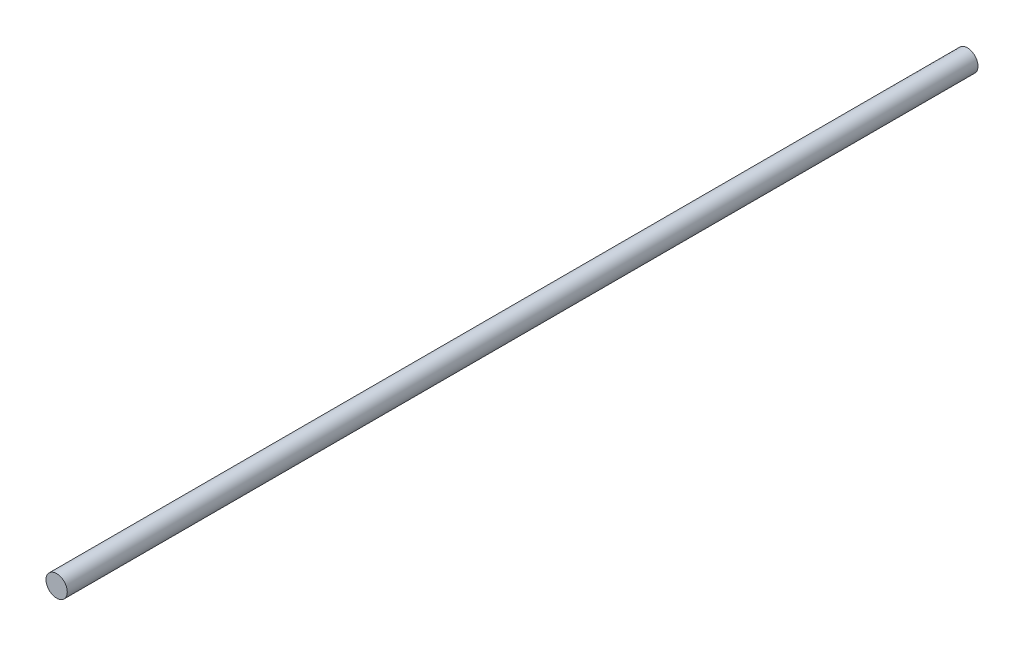
SolidWorks part; units mm, degrees
material "Plain Carbon Steel"
ref_plane "Front Plane" through (0, 0, 0) normal (0, 0, 1) x (1, 0, 0)
ref_plane "Top Plane" through (0, 0, 0) normal (0, 1, 0) x (1, 0, 0)
ref_plane "Right Plane" through (0, 0, 0) normal (1, 0, 0) x (0, 0, -1)
sketch "Sketch1" plane through (0, 0, 0) normal (0, 0, 1) x (1, 0, 0)
  circle A0 centre (0, 0) radius 4
  dimension "D1" = 8
extrude "Boss-Extrude1" add sketch "Sketch1" along normal blind 342
